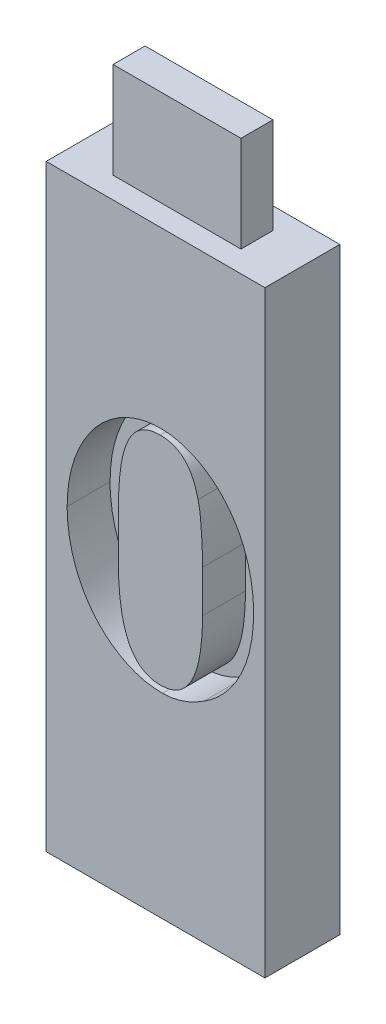
SolidWorks part; units mm, degrees
ref_plane "Front Plane" through (0, 0, 0) normal (0, 0, 1) x (1, 0, 0)
ref_plane "Top Plane" through (0, 0, 0) normal (0, 1, 0) x (1, 0, 0)
ref_plane "Right Plane" through (0, 0, 0) normal (1, 0, 0) x (0, 0, -1)
sketch "Sketch1" plane through (0, 0, 0) normal (0, 0, 1) x (1, 0, 0)
  line L1 (-8.69, -23.749) -> (8.69, -23.749)
  line L2 (-8.69, -23.749) -> (-8.69, 23.749)
  line L3 (-8.69, 23.749) -> (8.69, 23.749)
  line L4 (8.69, -23.749) -> (8.69, 23.749)
  line L5 (-8.69, -23.749) -> (8.69, 23.749) construction
  line L6 (-8.69, 23.749) -> (8.69, -23.749) construction
  point P0 (0, 0)
  dimension "D1" = 17.38
  dimension "D2" = 47.498
extrude "Boss-Extrude1" add sketch "Sketch1" along normal blind 5.95
sketch "Sketch2" plane through (0, 0, 5.95) normal (0, 0, 1) x (1, 0, 0)
  line L0 (0, 23.749) -> (0, -23.749) construction
  line L1 (8.69, 23.749) -> (-8.69, 23.749) construction
  line L2 (-8.69, -23.749) -> (8.69, -23.749) construction
  line L3 (0, -23.749) -> (0, 0) construction
  line L4 (0, 0) -> (-8.69, 0) construction
  line L5 (-8.69, 23.749) -> (-8.69, -23.749) construction
  line L6 (-8.69, 0) -> (8.69, 0) construction
  line L7 (8.69, -23.749) -> (8.69, 23.749) construction
  line L8 (-8.69, -23.749) -> (8.69, -23.749) construction
  line L9 (-8.69, -21.209) -> (8.69, -21.209) construction
  line L10 (-8.69, -18.669) -> (8.69, -18.669) construction
  line L11 (-8.69, -16.129) -> (8.69, -16.129) construction
  line L12 (-8.69, -13.589) -> (8.69, -13.589) construction
  line L13 (-8.69, -11.049) -> (8.69, -11.049) construction
  line L14 (-8.69, -8.509) -> (8.69, -8.509) construction
  line L15 (-8.69, -5.969) -> (8.69, -5.969) construction
  line L16 (-8.69, -3.429) -> (8.69, -3.429) construction
  line L17 (-8.69, -0.889) -> (8.69, -0.889) construction
  line L18 (-8.69, 1.651) -> (8.69, 1.651) construction
  line L19 (-8.69, 4.191) -> (8.69, 4.191) construction
  line L20 (-8.69, 6.731) -> (8.69, 6.731) construction
  line L21 (-8.69, 9.271) -> (8.69, 9.271) construction
  line L22 (-8.69, 11.811) -> (8.69, 11.811) construction
  line L23 (-8.69, 14.351) -> (8.69, 14.351) construction
  line L24 (-8.69, 16.891) -> (8.69, 16.891) construction
  line L25 (-8.69, 19.431) -> (8.69, 19.431) construction
  line L26 (-8.69, 21.971) -> (8.69, 21.971) construction
  line L27 (-8.69, 23.749) -> (-8.69, -23.749) construction
  line L28 (-6.15, 23.749) -> (-6.15, -23.749) construction
  line L29 (-3.61, 23.749) -> (-3.61, -23.749) construction
  line L30 (-1.07, 23.749) -> (-1.07, -23.749) construction
  line L31 (1.47, 23.749) -> (1.47, -23.749) construction
  line L32 (4.01, 23.749) -> (4.01, -23.749) construction
  line L33 (6.55, 23.749) -> (6.55, -23.749) construction
  text T0 "0\r\n" font "Engravers MT" height in points 72
  dimension "D1" = 19
  dimension "D2" = 2.54
  dimension "D4" = 2.54
  dimension "D3" = 7
extrude "Cut-Extrude1" cut sketch "Sketch2" against normal blind 3.41
sketch "Sketch3" plane through (0, 23.749, 0) normal (0, 1, 0) x (1, 0, 0)
  line L0 (0, 0) -> (0, -5.95) construction
  line L1 (8.69, -5.95) -> (-8.69, -5.95) construction
  line L2 (0, -5.95) -> (0, -2.975) construction
  line L3 (0, -2.975) -> (-8.69, -2.975) construction
  line L4 (-8.69, -5.95) -> (-8.69, 0) construction
  line L5 (-8.69, -2.975) -> (8.69, -2.975) construction
  line L6 (8.69, -5.95) -> (8.69, 0) construction
  line L8 (-5.08, -4.245) -> (5.08, -4.245)
  line L9 (-5.08, -4.245) -> (-5.08, -1.705)
  line L10 (-5.08, -1.705) -> (5.08, -1.705)
  line L11 (5.08, -4.245) -> (5.08, -1.705)
  line L12 (-5.08, -4.245) -> (5.08, -1.705) construction
  line L13 (-5.08, -1.705) -> (5.08, -4.245) construction
  dimension "D1" = 2.54
  dimension "D2" = 10.16
extrude "Boss-Extrude2" add sketch "Sketch3" along normal blind 7.62
